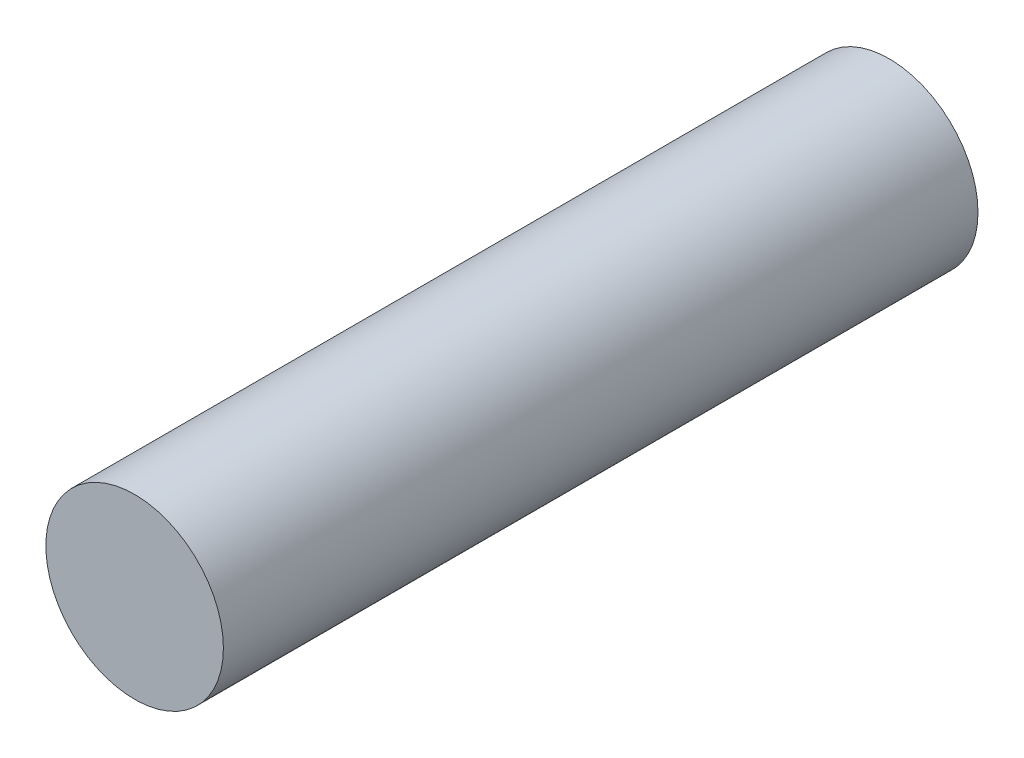
SolidWorks part; units mm, degrees
ref_plane "前视基准面" through (0, 0, 0) normal (0, 0, 1) x (1, 0, 0)
ref_plane "上视基准面" through (0, 0, 0) normal (0, 1, 0) x (1, 0, 0)
ref_plane "右视基准面" through (0, 0, 0) normal (1, 0, 0) x (0, 0, -1)
sketch "草图1" plane through (0, 0, 0) normal (0, 0, 1) x (1, 0, 0)
  circle A0 centre (0, 0) radius 2
extrude "凸台-拉伸1" add sketch "草图1" along normal blind 17
